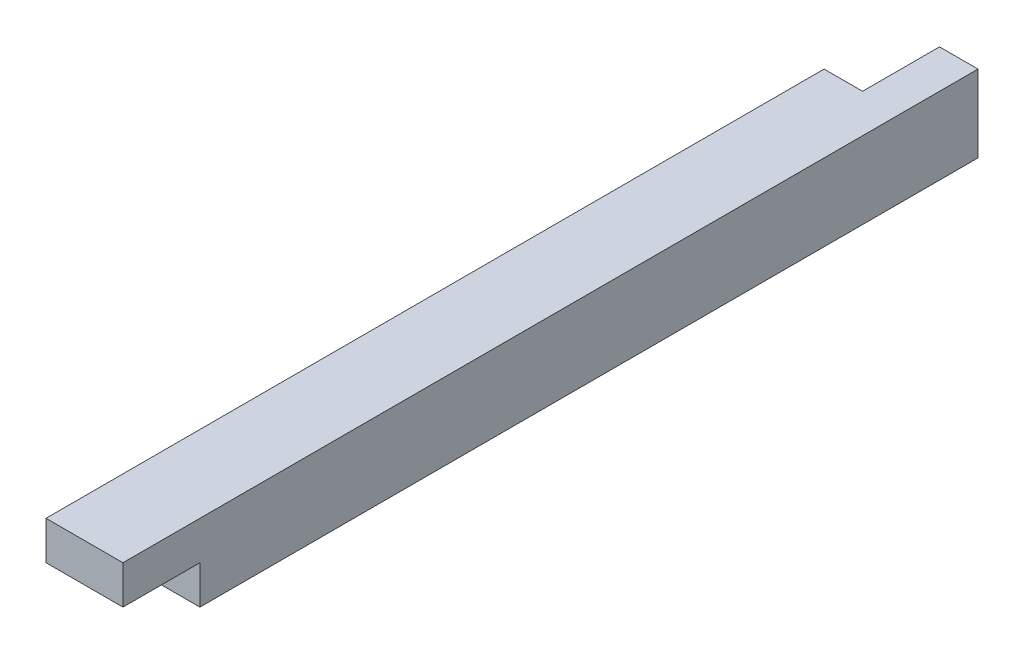
SolidWorks part; units mm, degrees
ref_plane "Front Plane" through (0, 0, 0) normal (0, 0, 1) x (1, 0, 0)
ref_plane "Top Plane" through (0, 0, 0) normal (0, 1, 0) x (1, 0, 0)
ref_plane "Right Plane" through (0, 0, 0) normal (1, 0, 0) x (0, 0, -1)
sketch "Sketch1" plane through (0, 0, 0) normal (0, 0, 1) x (1, 0, 0)
  line L1 (0, 0) -> (90, 0)
  line L2 (0, 0) -> (0, 90)
  line L3 (0, 90) -> (90, 90)
  line L4 (90, 0) -> (90, 90)
  dimension "D1" = 90
  dimension "D2" = 90
extrude "Boss-Extrude1" add sketch "Sketch1" along normal blind 1000
sketch "Sketch3" plane through (0, 0, 0) normal (0, -1, 0) x (1, 0, 0)
  line L0 (90, 1000) -> (90, 0) construction
  line L1 (0, 1000) -> (90, 1000)
  line L2 (0, 1000) -> (0, 910)
  line L3 (0, 910) -> (90, 910)
  line L4 (90, 1000) -> (90, 910)
  dimension "D1" = 90
extrude "Cut-Extrude1" cut sketch "Sketch3" against normal blind 45
sketch "Sketch4" plane through (0, 0, 0) normal (-1, 0, 0) x (0, 0, 1)
  line L0 (1000, 90) -> (0, 90) construction
  line L1 (0, 0) -> (90, 0)
  line L2 (0, 0) -> (0, 90)
  line L3 (0, 90) -> (90, 90)
  line L4 (90, 0) -> (90, 90)
  dimension "D1" = 90
extrude "Cut-Extrude2" cut sketch "Sketch4" against normal blind 45
